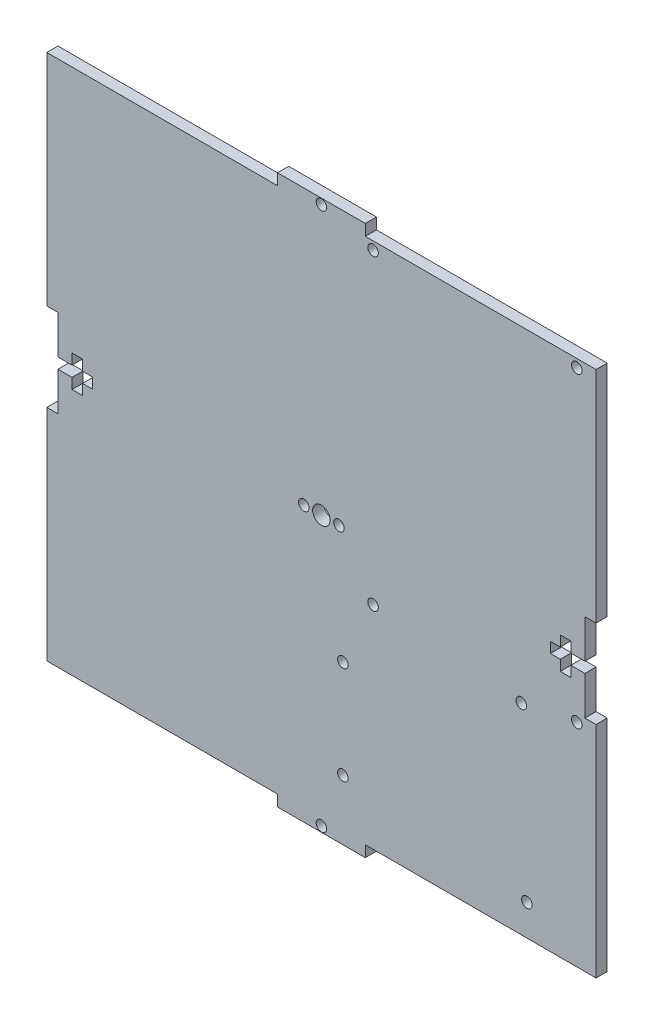
SolidWorks part; units mm, degrees
ref_plane "Front Plane" through (0, 0, 0) normal (0, 0, 1) x (1, 0, 0)
ref_plane "Top Plane" through (0, 0, 0) normal (0, 1, 0) x (1, 0, 0)
ref_plane "Right Plane" through (0, 0, 0) normal (1, 0, 0) x (0, 0, -1)
sketch "Sketch1" plane through (0, 0, 0) normal (0, 0, 1) x (1, 0, 0)
  line L0 (-12.5, 25) -> (12.5, 25) construction
  line L1 (-78.18, 75) -> (-12.5, 75)
  line L2 (-78.18, 75) -> (-78.18, 12.5)
  line L3 (-78.18, -75) -> (-12.5, -75)
  line L4 (78.18, 75) -> (78.18, 12.5)
  line L5 (-78.18, 75) -> (78.18, -75) construction
  line L6 (-78.18, -75) -> (78.18, 75) construction
  line L11 (12.5, 75) -> (12.5, 78.18)
  line L12 (12.5, 78.18) -> (-12.5, 78.18)
  line L17 (-12.5, 75) -> (-12.5, 78.18)
  line L18 (12.5, 75) -> (78.18, 75)
  line L25 (0, 100) -> (0, -75) construction
  line L26 (-100, 0) -> (100, 0) construction
  line L27 (-75, -1.5) -> (-75, -12.5)
  line L28 (-75, 12.5) -> (-78.18, 12.5)
  line L29 (-75, 12.5) -> (-75, 1.5)
  line L30 (-75, -12.5) -> (-78.18, -12.5)
  line L32 (-75, 12.5) -> (-78.18, -12.5) construction
  line L33 (-75, -12.5) -> (-78.18, 12.5) construction
  line L34 (-65.18, 1.5) -> (-68, 1.5)
  line L35 (-65.18, 1.5) -> (-65.18, -1.5)
  line L36 (-65.18, -1.5) -> (-68, -1.5)
  line L38 (-65.18, 1.5) -> (-75, -1.5) construction
  line L39 (-65.18, -1.5) -> (-75, 1.5) construction
  line L44 (-71, 4.5) -> (-68, 4.5)
  line L45 (-71, 4.5) -> (-71, 1.5)
  line L46 (-71, -4.5) -> (-68, -4.5)
  line L47 (-68, 4.5) -> (-68, 1.5)
  line L48 (-71, 4.5) -> (-68, -4.5) construction
  line L49 (-71, -4.5) -> (-68, 4.5) construction
  line L50 (-71, -1.5) -> (-71, -4.5)
  line L51 (-68, -1.5) -> (-68, -4.5)
  line L52 (-71, 1.5) -> (-75, 1.5)
  line L53 (-71, -1.5) -> (-75, -1.5)
  line L54 (65.18, 1.5) -> (68, 1.5)
  line L55 (68, 4.5) -> (68, 1.5)
  line L56 (71, 4.5) -> (68, 4.5)
  line L57 (71, 4.5) -> (71, 1.5)
  line L58 (71, 1.5) -> (75, 1.5)
  line L59 (75, 12.5) -> (75, 1.5)
  line L60 (75, 12.5) -> (78.18, 12.5)
  line L62 (75, -12.5) -> (78.18, -12.5)
  line L63 (75, -1.5) -> (75, -12.5)
  line L64 (71, -1.5) -> (75, -1.5)
  line L65 (71, -1.5) -> (71, -4.5)
  line L66 (71, -4.5) -> (68, -4.5)
  line L67 (68, -1.5) -> (68, -4.5)
  line L68 (65.18, -1.5) -> (68, -1.5)
  line L69 (65.18, 1.5) -> (65.18, -1.5)
  line L70 (-78.18, -12.5) -> (-78.18, -75)
  line L71 (78.18, -12.5) -> (78.18, -75)
  line L72 (0, -78.18) -> (0, -75) construction
  line L74 (12.5, -75) -> (12.5, -78.18)
  line L75 (12.5, -78.18) -> (-12.5, -78.18)
  line L76 (-12.5, -75) -> (-12.5, -78.18)
  line L77 (12.5, -76.59) -> (-12.5, -76.59) construction
  line L78 (12.5, -75) -> (78.18, -75)
  circle A2 centre (0, -76.59) radius 1.5
  circle A3 centre (0, 76.59) radius 1.5
  point P0 (0, 0)
  point P6 (-50, 50)
  point P11 (50, 50)
  point P16 (0, 0)
  point P27 (0, 25)
  point P30 (-76.59, 0)
  point P35 (-70.09, 0)
  point P40 (-70.09, 0)
  point P41 (-69.5, 0)
  dimension "D13" = 25
  dimension "D23" = 3
  dimension "D1" = 150
  dimension "D2" = 156.36
  dimension "D3" = 9
  dimension "D9" = 50
  dimension "D10" = 50
  dimension "D14" = 50
  dimension "D15" = 25
  dimension "D16" = 13
  dimension "D17" = 3.18
  dimension "D18" = 3
  dimension "D19" = 4
  dimension "D20" = 3
  dimension "D21" = 3.18
  dimension "D22" = 25
extrude "Boss-Extrude1" add sketch "Sketch1" along normal blind 3.18
sketch "Sketch2" plane through (0, 0, 3.18) normal (0, 0, 1) x (1, 0, 0)
  circle A0 centre (0, 0) radius 2.5
  circle A3 centre (-5, 0) radius 1.5
  circle A4 centre (5, 0) radius 1.5
  dimension "D1" = 5
  dimension "D2" = 3
  dimension "D3" = 3
extrude "Cut-Extrude1" cut sketch "Sketch2" against normal blind 20
sketch "Sketch3" plane through (0, 0, 3.18) normal (0, 0, 1) x (1, 0, 0)
  circle A0 centre (56.9, -17.8478) radius 1.5
  circle A1 centre (58.5, -66.1478) radius 1.5
  circle A2 centre (6.1, -33.1478) radius 1.5
  circle A3 centre (6.1, -61.0478) radius 1.5
  dimension "D1" = 3
  dimension "D2" = 3
  dimension "D3" = 3
  dimension "D4" = 3
extrude "Cut-Extrude2" cut sketch "Sketch3" against normal blind 20
sketch "Sketch4" plane through (0, 0, 3.18) normal (0, 0, 1) x (1, 0, 0)
  line L0 (-68, -4.5) -> (-71, -4.5) construction
  line L1 (-78.18, -12.5) -> (-78.18, -75) construction
  circle A0 centre (-73.18, -44.5) radius 1.5
  circle A1 centre (-73.18, -57.5) radius 1.5
  dimension "D1" = 3
  dimension "D2" = 3
  dimension "D3" = 13
  dimension "D4" = 40
  dimension "D5" = 5
  dimension "D6" = 5
sketch "Sketch5" plane through (0, 0, 3.18) normal (0, 0, 1) x (1, 0, 0)
  circle A0 centre (14.7029, 72.6971) radius 1.5
  circle A1 centre (72.6971, 72.6971) radius 1.5
  circle A2 centre (14.7029, -14.6971) radius 1.5
  circle A3 centre (72.6971, -14.6971) radius 1.5
  dimension "D1" = 3
  dimension "D2" = 3
  dimension "D3" = 3
  dimension "D4" = 3
extrude "Cut-Extrude4" cut sketch "Sketch5" against normal blind 4
